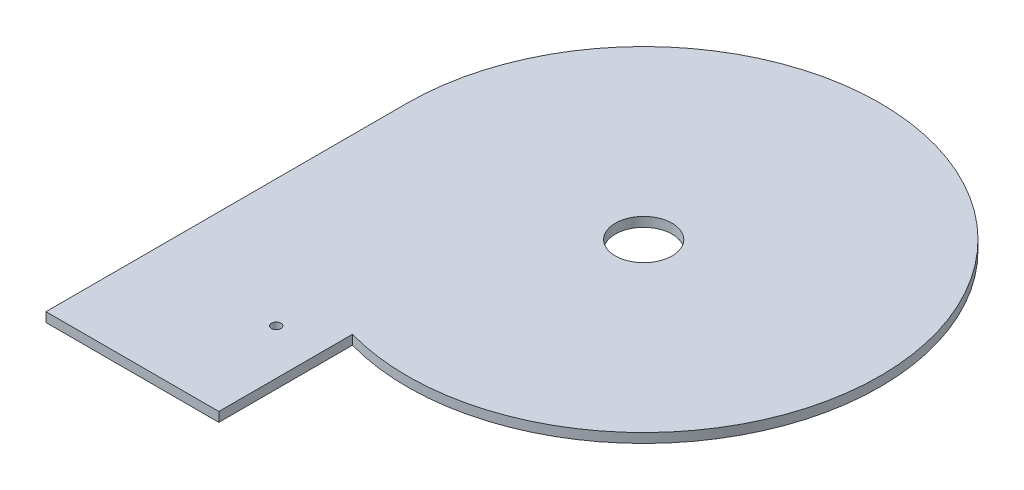
SolidWorks part; units mm, degrees
ref_plane "Front Plane" through (0, 0, 0) normal (0, 0, 1) x (1, 0, 0)
ref_plane "Top Plane" through (0, 0, 0) normal (0, 1, 0) x (1, 0, 0)
ref_plane "Right Plane" through (0, 0, 0) normal (1, 0, 0) x (0, 0, -1)
sketch "Sketch1" plane through (0, 0, 0) normal (0, 1, 0) x (1, 0, 0)
  circle A0 centre (0, 0) radius 50
extrude "Boss-Extrude1" add sketch "Sketch1" along normal blind 2
sketch "Sketch2" plane through (0, 2, 0) normal (0, 1, 0) x (1, 0, 0)
  circle A0 centre (0, 0) radius 6
extrude "Cut-Extrude1" cut sketch "Sketch2" against normal blind 2
sketch "Sketch3" plane through (0, 0, 0) normal (0, -1, 0) x (1, 0, 0)
  line L1 (-50, 0) -> (-13.4445, 0)
  line L2 (-50, 0) -> (-50, 76.4199)
  line L3 (-50, 76.4199) -> (-13.4445, 76.4199)
  line L4 (-13.4445, 0) -> (-13.4445, 76.4199)
  circle A0 centre (0, 0) radius 50 construction
extrude "Boss-Extrude2" add sketch "Sketch3" against normal through all
sketch "Sketch4" plane through (0, 2, 0) normal (0, 1, 0) x (1, 0, 0)
  line L4 (-26, -48.23) -> (-26, -61.13)
  line L5 (-20.1, -48.23) -> (-26, -48.23)
  line L6 (-20.1, -61.13) -> (-20.1, -48.23)
  line L7 (-26, -61.13) -> (-20.1, -61.13)
  line L8 (-26, -48.23) -> (-26, -61.13)
  line L9 (-20.1, -48.23) -> (-26, -48.23)
  line L10 (-20.1, -61.13) -> (-20.1, -48.23)
  line L11 (-26, -61.13) -> (-20.1, -61.13)
  dimension "D1" = 0
sketch "Sketch5" plane through (0, 0, 0) normal (0, -1, 0) x (1, 0, 0)
  circle A0 centre (-23.05, 54.68) radius 1 construction
  circle A1 centre (-23.05, 54.68) radius 1
ref_plane "Plane1" through (21.52, -68.6, 73.8609) normal (1, 0, 0) x (0, 0, -1)
sketch "Sketch7" plane through (0, 2, 0) normal (0, 1, 0) x (1, 0, 0)
  line L4 (-26, -48.23) -> (-26, -61.13)
  line L5 (-20.1, -48.23) -> (-26, -48.23)
  line L6 (-20.1, -61.13) -> (-20.1, -48.23)
  line L7 (-26, -61.13) -> (-20.1, -61.13)
  line L8 (-26, -48.23) -> (-26, -61.13)
  line L9 (-20.1, -48.23) -> (-26, -48.23)
  line L10 (-20.1, -61.13) -> (-20.1, -48.23)
  line L11 (-26, -61.13) -> (-20.1, -61.13)
  dimension "D1" = 0
sketch "Sketch8" plane through (0, 0, 0) normal (0, -1, 0) x (1, 0, 0)
  line L0 (-26, 61.13) -> (-20.1, 61.13) construction
  line L1 (-26, 48.23) -> (-26, 61.13) construction
  circle A0 centre (-23.05, 54.68) radius 1
  dimension "D1" = 6.45
  dimension "D2" = 2.95
extrude "Cut-Extrude2" cut sketch "Sketch8" against normal up to next
